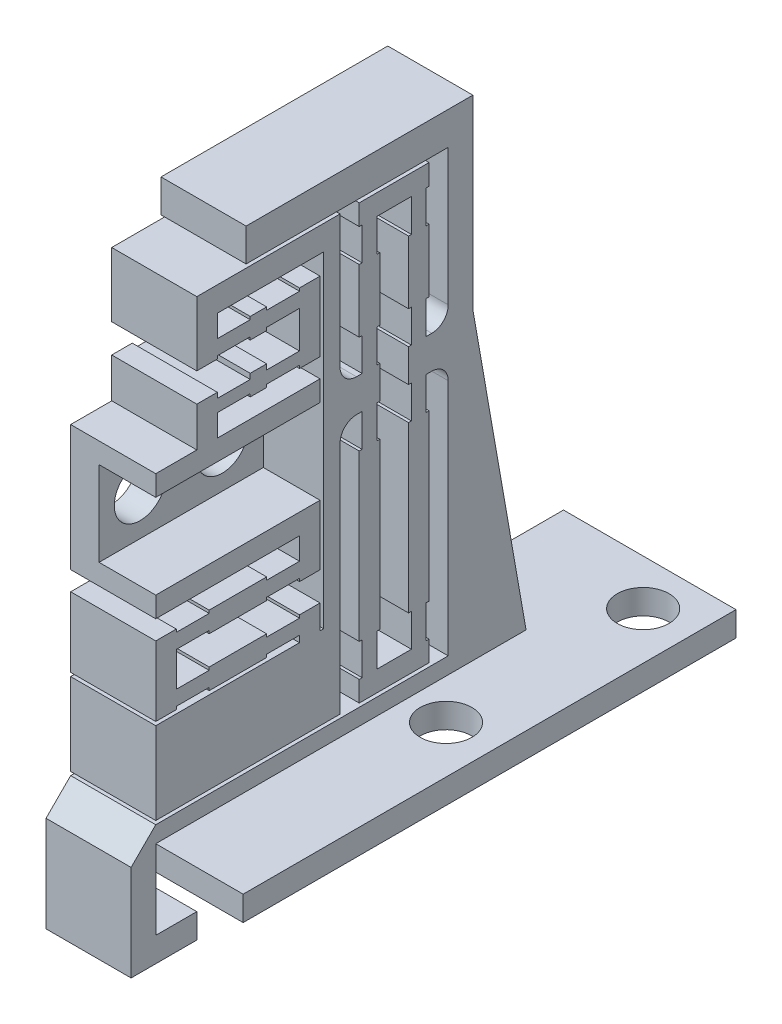
SolidWorks part; units mm, degrees
other "Markup1"
sketch "Sketch8" plane through (10.5, 0, 3) normal (0.7095, 0.0467, 0.7031) x (0.7044, -0.0184, -0.7096)
ref_plane "Front Plane" through (0, 0, 0) normal (0, 0, 1) x (1, 0, 0)
ref_plane "Top Plane" through (0, 0, 0) normal (0, 1, 0) x (1, 0, 0)
ref_plane "Right Plane" through (0, 0, 0) normal (1, 0, 0) x (0, 0, -1)
sketch "Sketch1" plane through (0, 0, 0) normal (1, 0, 0) x (0, 0, -1)
  line L0 (-1.75, -10.3033) -> (4.5, -10.3033)
  line L1 (4.5, -10.3033) -> (4.5, -20.37)
  line L2 (-5.5, -10.3033) -> (-5.5, -17.9533)
  line L3 (-5.5, -17.9533) -> (3.25, -17.9533)
  line L56 (3.25, -19.295) -> (1.25, -19.295)
  line L57 (-4.25, -20.195) -> (-4.25, -22.295)
  line L58 (-4.25, -22.295) -> (-2.25, -22.295)
  line L59 (4.5, -22.12) -> (4.5, -23.59)
  line L60 (3.25, -17.9533) -> (3.25, -19.295)
  line L61 (1.25, -19.295) -> (1.25, -19.12)
  line L62 (-5.5, -19.12) -> (-5.5, -23.37)
  line L63 (-2.25, -22.295) -> (-2.25, -22.12)
  line L64 (4.72, -3.72) -> (4.72, -23.59)
  line L65 (-1.75, -8.9617) -> (0.25, -8.9617)
  line L66 (3.25, -8.2117) -> (3.25, -5.9617)
  line L67 (3.25, -5.9617) -> (1.25, -5.9617)
  line L68 (-3, -6.1367) -> (-3, -2.22)
  line L69 (-1.75, -10.3033) -> (-1.75, -8.9617)
  line L70 (0.25, -8.9617) -> (0.25, -9.1367)
  line L71 (4.5, -9.1367) -> (4.5, -4.8867)
  line L72 (1.25, -5.9617) -> (1.25, -6.1367)
  line L73 (-1.75, -5.0617) -> (-1.75, -3.72)
  line L74 (-1.75, -3.72) -> (4.72, -3.72)
  line L75 (-3, -2.22) -> (5.72, -2.22)
  line L76 (0.25, -9.1367) -> (1.25, -9.1367)
  line L77 (1.25, -9.1367) -> (1.25, -8.9617)
  line L78 (1.25, -8.9617) -> (3.25, -8.9617)
  line L79 (3.25, -8.9617) -> (3.25, -9.1367)
  line L80 (3.25, -9.1367) -> (4.5, -9.1367)
  line L81 (3.25, -8.2117) -> (1.25, -8.2117)
  line L82 (1.25, -8.2117) -> (1.25, -7.8867)
  line L83 (1.25, -7.8867) -> (0.25, -7.8867)
  line L84 (0.25, -7.8867) -> (0.25, -8.2117)
  line L85 (0.25, -8.2117) -> (-1.75, -8.2117)
  line L86 (-1.75, -8.2117) -> (-1.75, -7.8867)
  line L87 (-1.75, -7.8867) -> (-3, -7.8867)
  line L88 (1.25, -6.1367) -> (0.25, -6.1367)
  line L89 (0.25, -6.1367) -> (0.25, -5.9617)
  line L90 (0.25, -5.9617) -> (-1.75, -5.9617)
  line L91 (-1.75, -5.9617) -> (-1.75, -6.1367)
  line L92 (-1.75, -6.1367) -> (-3, -6.1367)
  line L93 (-1.75, -5.0617) -> (0.25, -5.0617)
  line L94 (0.25, -5.0617) -> (0.25, -4.8867)
  line L95 (0.25, -4.8867) -> (1.25, -4.8867)
  line L96 (1.25, -4.8867) -> (1.25, -5.0617)
  line L97 (1.25, -5.0617) -> (3.25, -5.0617)
  line L98 (3.25, -5.0617) -> (3.25, -4.8867)
  line L99 (3.25, -4.8867) -> (4.5, -4.8867)
  line L100 (1.25, -19.12) -> (-2.25, -19.12)
  line L101 (-2.25, -19.12) -> (-2.25, -19.295)
  line L102 (-2.25, -19.295) -> (-4.25, -19.295)
  line L103 (-4.25, -19.295) -> (-4.25, -19.12)
  line L104 (-4.25, -19.12) -> (-5.5, -19.12)
  line L105 (4.5, -20.37) -> (3.25, -20.37)
  line L106 (3.25, -20.37) -> (3.25, -20.195)
  line L107 (3.25, -20.195) -> (1.25, -20.195)
  line L108 (1.25, -20.195) -> (1.25, -20.37)
  line L109 (1.25, -20.37) -> (-2.25, -20.37)
  line L110 (-2.25, -20.37) -> (-2.25, -20.195)
  line L111 (-2.25, -20.195) -> (-4.25, -20.195)
  line L112 (-2.25, -22.12) -> (1.25, -22.12)
  line L113 (1.25, -22.12) -> (1.25, -22.295)
  line L114 (1.25, -22.295) -> (3.25, -22.295)
  line L115 (3.25, -22.295) -> (3.25, -22.12)
  line L116 (3.25, -22.12) -> (4.5, -22.12)
  line L117 (-5.5, -23.37) -> (-4.25, -23.37)
  line L118 (-4.25, -23.37) -> (-4.25, -23.195)
  line L119 (-4.25, -23.195) -> (-2.25, -23.195)
  line L120 (-2.25, -23.195) -> (-2.25, -23.37)
  line L121 (-2.25, -23.37) -> (1.25, -23.37)
  line L122 (1.25, -23.37) -> (1.25, -23.195)
  line L123 (1.25, -23.195) -> (3.25, -23.195)
  line L124 (3.25, -23.195) -> (3.25, -23.59)
  line L125 (4.72, -23.59) -> (4.5, -23.59)
  line L126 (3.25, -23.59) -> (-5.5, -23.59)
  line L127 (-5.5, -23.59) -> (-5.5, -28.59)
  line L128 (-5.5, -28.59) -> (5.72, -28.59)
  line L130 (10.0617, -27.34) -> (7.9617, -27.34)
  line L131 (7.9617, -27.34) -> (7.9617, -25.34)
  line L132 (7.9617, -25.34) -> (8.1367, -25.34)
  line L133 (8.1367, -25.34) -> (8.1367, -15.3033)
  line L134 (8.1367, -15.3033) -> (7.9617, -15.3033)
  line L135 (7.9617, -15.3033) -> (7.9617, -13.3033)
  line L137 (10.0617, -13.3033) -> (10.0617, -15.3033)
  line L138 (10.0617, -15.3033) -> (9.8867, -15.3033)
  line L139 (9.8867, -15.3033) -> (9.8867, -25.34)
  line L140 (9.8867, -25.34) -> (10.0617, -25.34)
  line L141 (10.0617, -25.34) -> (10.0617, -27.34)
  line L145 (7.0617, -27.34) -> (6.8867, -27.34)
  line L146 (7.0617, -27.34) -> (7.0617, -25.34)
  line L147 (7.0617, -25.34) -> (6.8867, -25.34)
  line L148 (6.8867, -25.34) -> (6.8867, -15.3033)
  line L149 (6.8867, -15.3033) -> (7.0617, -15.3033)
  line L150 (7.0617, -13.3033) -> (6.72, -13.3033)
  line L151 (7.0617, -15.3033) -> (7.0617, -13.3033)
  line L153 (6.72, -11.3033) -> (7.0617, -11.3033)
  line L155 (11.3033, -13.3033) -> (10.9617, -13.3033)
  line L156 (10.9617, -13.3033) -> (10.9617, -15.3033)
  line L157 (10.9617, -15.3033) -> (11.1367, -15.3033)
  line L158 (11.1367, -15.3033) -> (11.1367, -25.34)
  line L159 (11.1367, -25.34) -> (10.9617, -25.34)
  line L160 (10.9617, -25.34) -> (10.9617, -27.34)
  line L168 (12.3033, -28.81) -> (12.3033, -14.3033)
  line L179 (12.3033, -28.81) -> (-5.5, -28.81)
  line L184 (-5.5, -31.31) -> (17.3033, -31.31)
  line L187 (13.8033, 0) -> (0, 0)
  line L189 (5.72, -28.59) -> (5.72, -14.3033)
  line L190 (12.3033, -2) -> (0, -2)
  line L191 (0, -2) -> (0, 0)
  line L192 (11.1367, -27.34) -> (10.9617, -27.34)
  line L198 (6.8867, -27.34) -> (6.8867, -28.59)
  line L199 (11.1367, -27.34) -> (11.1367, -28.59)
  line L200 (11.1367, -28.59) -> (6.8867, -28.59)
  line L201 (5.72, -10.3033) -> (5.72, -2.22)
  line L203 (9.8867, -13.3033) -> (9.8867, -11.3033)
  line L204 (8.1367, -13.3033) -> (8.1367, -11.3033)
  line L208 (-5.5, -31.31) -> (-5.5, -34.64)
  line L209 (-5.5, -34.64) -> (-3, -34.64)
  line L210 (-3, -34.64) -> (-3, -36.14)
  line L211 (-3, -36.14) -> (-7, -36.14)
  line L212 (-7, -36.14) -> (-7, -30.31)
  line L213 (-7, -30.31) -> (-5.5, -28.81)
  line L214 (-3, -10.3033) -> (-5.5, -10.3033)
  line L215 (-3, -10.3033) -> (-3, -7.8867)
  line L220 (7.9617, -11.3033) -> (7.9617, -9.3033)
  line L221 (7.9617, -9.3033) -> (8.1367, -9.3033)
  line L222 (8.1367, -9.3033) -> (8.1367, -5.47)
  line L223 (8.1367, -5.47) -> (7.9617, -5.47)
  line L224 (7.9617, -5.47) -> (7.9617, -3.47)
  line L225 (7.9617, -3.47) -> (10.0617, -3.47)
  line L226 (10.0617, -3.47) -> (10.0617, -5.47)
  line L227 (10.0617, -5.47) -> (9.8867, -5.47)
  line L228 (9.8867, -5.47) -> (9.8867, -9.3033)
  line L229 (9.8867, -9.3033) -> (10.0617, -9.3033)
  line L230 (10.0617, -9.3033) -> (10.0617, -11.3033)
  line L231 (10.0617, -11.3033) -> (9.8867, -11.3033)
  line L232 (7.0617, -11.3033) -> (7.0617, -9.3033)
  line L233 (7.0617, -9.3033) -> (6.8867, -9.3033)
  line L234 (6.8867, -9.3033) -> (6.8867, -5.47)
  line L235 (6.8867, -5.47) -> (7.0617, -5.47)
  line L236 (7.0617, -5.47) -> (7.0617, -3.47)
  line L237 (7.0617, -3.47) -> (6.8867, -3.47)
  line L238 (6.8867, -3.47) -> (6.8867, -2.22)
  line L239 (6.8867, -2.22) -> (11.1367, -2.22)
  line L240 (11.1367, -2.22) -> (11.1367, -3.47)
  line L241 (11.1367, -3.47) -> (10.9617, -3.47)
  line L242 (10.9617, -3.47) -> (10.9617, -5.47)
  line L243 (10.9617, -5.47) -> (11.1367, -5.47)
  line L244 (11.1367, -5.47) -> (11.1367, -9.3033)
  line L245 (11.1367, -9.3033) -> (10.9617, -9.3033)
  line L246 (10.9617, -9.3033) -> (10.9617, -11.3033)
  line L247 (10.9617, -11.3033) -> (11.3033, -11.3033)
  line L248 (12.3033, -10.3033) -> (12.3033, -2)
  line L250 (7.9617, -11.3033) -> (8.1367, -11.3033)
  line L251 (13.8033, 0) -> (13.8033, -11.31)
  line L252 (13.8033, -11.31) -> (17.3033, -31.31)
  line L253 (10.0617, -13.3033) -> (9.8867, -13.3033)
  line L255 (7.9617, -13.3033) -> (8.1367, -13.3033)
  arc A4 (11.3033, -13.3033) -> (12.3033, -14.3033) centre (11.3033, -14.3033) cw
  arc A6 (11.3033, -11.3033) -> (12.3033, -10.3033) centre (11.3033, -10.3033) ccw
  arc A7 (6.72, -11.3033) -> (5.72, -10.3033) centre (6.72, -10.3033) cw
  arc A8 (6.72, -13.3033) -> (5.72, -14.3033) centre (6.72, -14.3033) ccw
  point P120 (9.07, -2)
  point P140 (12.3033, -13.3033)
  point P159 (-2.375, -6.1367)
  point P172 (5.72, -11.3033)
  point P183 (5.72, -12.5533)
  point P189 (12.3033, -12.5533)
  point P199 (10.9617, -26.34)
  dimension "D61" = 1
  dimension "D3" = 4.25
  dimension "D4" = 0.175
  dimension "D5" = 1.25
  dimension "D6" = 0.9
  dimension "D7" = 1.75
  dimension "D8" = 0.175
  dimension "D9" = 0.9
  dimension "D10" = 1.1667
  dimension "D13" = 4.25
  dimension "D14" = 1.1667
  dimension "D15" = 0.175
  dimension "D16" = 1.25
  dimension "D17" = 0.75
  dimension "D18" = 1.75
  dimension "D19" = 0.175
  dimension "D21" = 0.9
  dimension "D22" = 1.1667
  dimension "D23" = 1.5
  dimension "D24" = 0.22
  dimension "D25" = 0.22
  dimension "D34" = 2.5
  dimension "D35" = 2
  dimension "D37" = 1.25
  dimension "D38" = 1.25
  dimension "D40" = 0.22
  dimension "D41" = 1.25
  dimension "D42" = 1.1667
  dimension "D43" = 0.175
  dimension "D44" = 0.9
  dimension "D45" = 1.75
  dimension "D46" = 0.175
  dimension "D47" = 0.9
  dimension "D48" = 1.25
  dimension "D12" = 7.65
  dimension "D20" = 1
  dimension "D27" = 1.1667
  dimension "D32" = 2
  dimension "D39" = 10
  dimension "D30" = 2
  dimension "D53" = 1.5
  dimension "D57" = 1.5
  dimension "D58" = 3.33
  dimension "D59" = 4
  dimension "D31" = 2
  dimension "D55" = 1.25
  dimension "D60" = 1
  dimension "D63" = 2
  dimension "D65" = 2.5
  dimension "D64" = 3
  dimension "D11" = 2
  dimension "D49" = 1.5
  dimension "D29" = 20
  dimension "D36" = 5
  dimension "D28" = 1.25
  dimension "D33" = 0.22
  dimension "D50" = 5
  dimension "D26" = 2
extrude "Boss-Extrude1" add sketch "Sketch1" along normal blind 5.18
sketch "Sketch2" plane through (0, 0, 5.5) normal (0, 0, 1) x (1, 0, 0)
  line L0 (5.18, -10.3033) -> (5.18, -17.9533) construction
  line L1 (5.18, -16.7033) -> (1.73, -16.7033)
  line L2 (5.18, -16.7033) -> (5.18, -11.5533)
  line L3 (5.18, -11.5533) -> (1.73, -11.5533)
  line L4 (1.73, -16.7033) -> (1.73, -11.5533)
  line L5 (5.18, -10.3033) -> (5.18, -17.9533) construction
  dimension "D1" = 3.45
  dimension "D2" = 1.25
  dimension "D3" = 1.25
extrude "Cut-Extrude4" cut sketch "Sketch2" against normal up to next
sketch "Sketch3" plane through (0, -31.31, 0) normal (0, -1, 0) x (1, 0, 0)
  line L1 (0, -24.5) -> (10.5, -24.5)
  line L2 (0, -24.5) -> (0, 5.5)
  line L3 (0, 5.5) -> (10.5, 5.5)
  line L4 (10.5, -24.5) -> (10.5, 5.5)
  line L5 (5.18, 5.5) -> (5.18, -17.3033) construction
  line L8 (0, 5.5) -> (0, -17.3033) construction
  circle A0 centre (7.62, -9.73) radius 1.575
  circle A1 centre (7.62, -21.73) radius 1.575
  dimension "D3" = 3.15
  dimension "D1" = 10.5
  dimension "D2" = 2.44
  dimension "D4" = 12
  dimension "D5" = 30
  dimension "D6" = 15.23
sketch "Sketch7" plane through (0, 0, 0) normal (-1, 0, 0) x (0, 0, 1)
  line L0 (3, -10.3033) -> (5.5, -10.3033) construction
  line L1 (5.5, -10.3033) -> (5.5, -17.9533) construction
  circle A0 centre (3, -14.1783) radius 1.575
  circle A1 centre (-2, -14.1783) radius 1.575
  dimension "D1" = 3.15
  dimension "D2" = 3.875
  dimension "D3" = 2.5
  dimension "D4" = 5
extrude "Cut-Extrude3" cut sketch "Sketch7" against normal up to next
extrude "Boss-Extrude2" add sketch "Sketch3" against normal blind 1.5
mirror "Mirror1" [suppressed]
delete or keep bodies "Body-Delete/Keep 1" [suppressed] type delete bodies bodies 111
equation "\"VerticalFlexureWidth\"= 1.3"
equation "\"VerticalFlexureGap\"= 1"
equation "\"VerticalDoubleFlexureWidth\"= 2 * \"VerticalFlexureWidth\" + \"VerticalFlexureGap\""
equation "\"HorizontalFlexureLength\"= 7"
equation "\"FlexureJointWidth\"= 1.25"
equation "\"HeadHeight\"= 7.5"
equation "\"VerticalFlexureLength\"= 18"
equation "\"MinGap\"= 0.22"
equation "\"BaseplateHeight+Tolerance\"= 3.33"
equation "\"HeadWidth\"=10"
equation "\"D1@Boss-Extrude1\"=5.18"
equation "\"HorizontalFlexureWidth\"= 1"
equation "\"HorizontalFlexureGap\"= 1"
equation "\"HorizontalDoubleFlexureWidth\"= 2 * \"HorizontalFlexureWidth\" + \"HorizontalFlexureGap\""
equation "\"FlexureWidth\"= 0.9"
equation "\"FlexureWideWidth\"=1.25"
equation "\"FlexureGap\"=1.75"
equation "\"TwinFlexureWidth\"= \"FlexureGap\" + 2 * \"FlexureWideWidth\""
equation "\"D3@Sketch1\"=\"TwinFlexureWidth\""
equation "\"FlexureNeckWidth\"= ( \"FlexureWideWidth\" - \"FlexureWidth\" ) / 2"
equation "\"D4@Sketch1\"=\"FlexureNeckWidth\""
equation "\"D5@Sketch1\"=\"FlexureWideWidth\""
equation "\"D6@Sketch1\"=\"FlexureWidth\""
equation "\"D7@Sketch1\"=\"FlexureGap\""
equation "\"D8@Sketch1\"=\"FlexureNeckWidth\""
equation "\"D9@Sketch1\"=\"FlexureWidth\""
equation "\"D10@Sketch1\"=\"FlexureGapEdge\""
equation "\"D13@Sketch1\"=\"TwinFlexureWidth\""
equation "\"D14@Sketch1\"=\"FlexureGapEdge\""
equation "\"D15@Sketch1\"=\"FlexureNeckWidth\""
equation "\"D16@Sketch1\"=\"FlexureWideWidth\""
equation "\"D19@Sketch1\"=\"FlexureNeckWidth\""
equation "\"D21@Sketch1\"=\"FlexureWidth\""
equation "\"D18@Sketch1\"=\"FlexureGap\""
equation "\"D22@Sketch1\"=\"FlexureGapEdge\""
equation "\"FlexureLength\"= 2"
equation "\"MainSupport\"=1.5"
equation "\"D23@Sketch1\"=\"MainSupport\""
equation "\"D24@Sketch1\"=\"MinGap\""
equation "\"D25@Sketch1\"=\"MinGap\""
equation "\"D35@Sketch1\"=\"FlexureLength\""
equation "\"D37@Sketch1\"=\"FlexureJointWidth\""
equation "\"D40@Sketch1\"=\"MinGap\""
equation "\"D41@Sketch1\"=\"FlexureWideWidth\""
equation "\"D42@Sketch1\"=\"FlexureGapEdge\""
equation "\"D43@Sketch1\"=\"FlexureNeckWidth\""
equation "\"D44@Sketch1\"=\"FlexureWidth\""
equation "\"D46@Sketch1\"=\"FlexureNeckWidth\""
equation "\"D47@Sketch1\"=\"FlexureWidth\""
equation "\"D48@Sketch1\"=\"FlexureWideWidth\""
equation "\"D27@Sketch1\"=\"FlexureGapEdge\""
equation "\"D32@Sketch1\"=\"FlexureLength\""
equation "\"D30@Sketch1\"=\"FlexureLength\""
equation "\"D53@Sketch1\"=\"MainSupport\""
equation "\"D57@Sketch1\"=\"MainSupport\""
equation "\"D58@Sketch1\"=\"BaseplateHeight+Tolerance\""
equation "\"D39@Sketch1\"=\"HeadWidth\""
equation "\"FlexureGapEdge\"= \"FlexureGap\" * ( 2 / 3 )"
equation "\"D55@Sketch1\"=\"FlexureJointWidth\""
equation "\"D63@Sketch1\"=\"FlexureLength\""
equation "\"FlexurePlateConnectionHeigh\"= 5.15 + 2.5"
equation "\"D12@Sketch1\"=\"FlexurePlateConnectionHeigh\""
equation "\"D45@Sketch1\"=\"FlexureGap\""
equation "\"D28@Sketch1\"=\"FlexureJointWidth\""
equation "\"D33@Sketch1\"=\"MinGap\""
